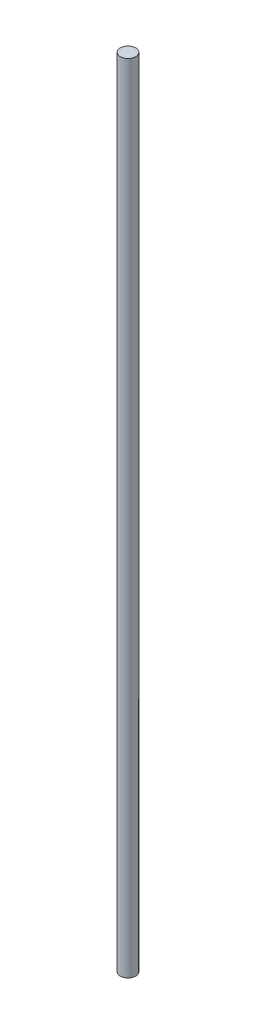
SolidWorks part; units mm, degrees
ref_plane "Front Plane" through (0, 0, 0) normal (0, 0, 1) x (1, 0, 0)
ref_plane "Top Plane" through (0, 0, 0) normal (0, 1, 0) x (1, 0, 0)
ref_plane "Right Plane" through (0, 0, 0) normal (1, 0, 0) x (0, 0, -1)
sketch "Sketch1" plane through (0, 0, 0) normal (0, 1, 0) x (1, 0, 0)
  circle A0 centre (0, 0) radius 3.175
  dimension "D1" = 6.35
extrude "Boss-Extrude1" add sketch "Sketch1" along normal blind 330.2
